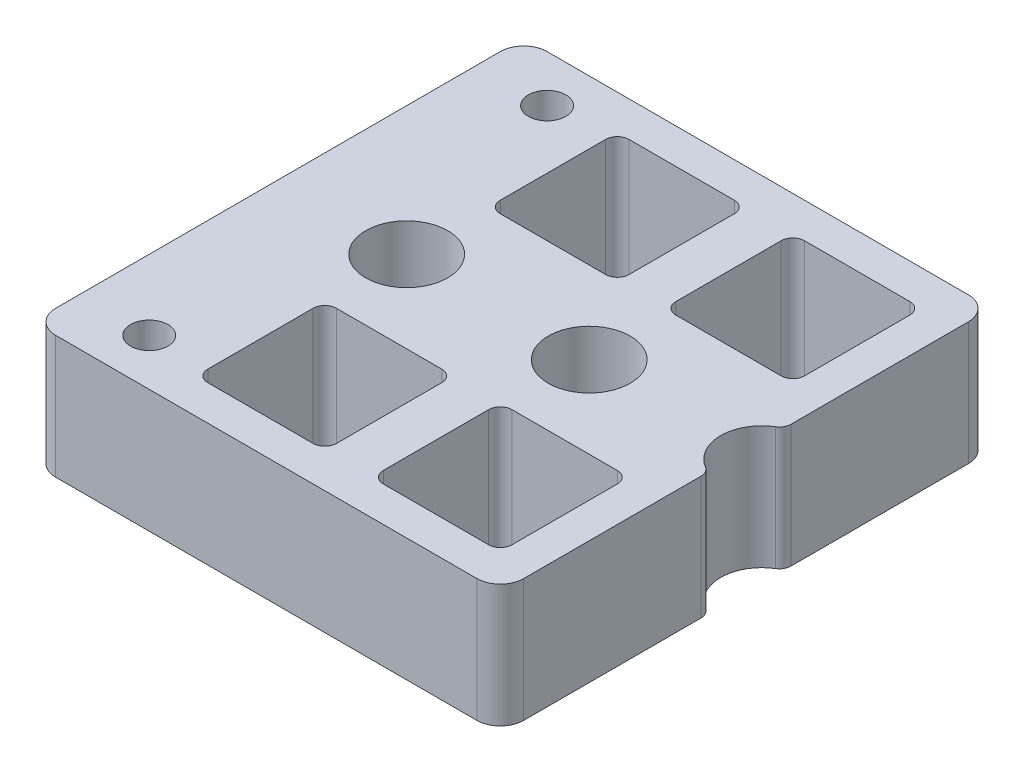
SolidWorks part; units mm, degrees
material "ABS"
ref_plane "前视基准面" through (0, 0, 0) normal (0, 0, 1) x (1, 0, 0)
ref_plane "上视基准面" through (0, 0, 0) normal (0, 1, 0) x (1, 0, 0)
ref_plane "右视基准面" through (0, 0, 0) normal (1, 0, 0) x (0, 0, -1)
other "Configuration Table"
sketch "草图1" plane through (0, 0, 0) normal (0, 1, 0) x (1, 0, 0)
  line L0 (-15, 19.7671) -> (-15, -49.3288) construction
  line L1 (-40, 45) -> (-25, 45)
  line L2 (-40, 45) -> (-40, -45) construction
  line L3 (-40, -45) -> (-25, -45)
  line L4 (-25, 45) -> (-25, -45)
  line L5 (-115, 21) -> (-41, 21) construction
  line L6 (-115, 21) -> (-115, -21)
  line L7 (-115, -21) -> (-41, -21) construction
  line L8 (-41, 21) -> (-41, -21) construction
  line L9 (0, 0) -> (-115, 0) construction
  line L10 (-115, 21) -> (-40, 45)
  line L11 (-115, -21) -> (-40, -45)
  line L12 (-98.5945, 21) -> (-40, 39.7502)
  line L13 (-40, 39.7502) -> (-40, 21)
  line L14 (-40, 21) -> (-98.5945, 21)
  line L15 (-40, -21) -> (-98.5945, -21)
  line L16 (-98.5945, -21) -> (-40, -39.7502)
  line L17 (-40, -39.7502) -> (-40, -21)
  line L18 (-32.5, 45) -> (-32.5, -45) construction
  line L19 (-79, 21) -> (-79, -21) construction
  line L20 (-45, 21) -> (-45, -21)
  line L21 (-115, -21) -> (-98.5945, -21)
  line L22 (-115, 21) -> (-98.5945, 21)
  line L23 (-85, 21) -> (-85, -21)
  circle A0 centre (-32.5, 0) radius 1.6
  circle A1 centre (-32.5, -30) radius 1.6
  circle A2 centre (-32.5, 30) radius 1.6
  circle A3 centre (-79, 17) radius 1.6
  circle A4 centre (-79, -17) radius 1.6
  circle A5 centre (-94, 0) radius 1.6
  circle A6 centre (-69, 0) radius 1.6
  dimension "D9" = 3.2
  dimension "D10" = 3.2
  dimension "D11" = 3.2
  dimension "D14" = 3.2
  dimension "D15" = 3.2
  dimension "D19" = 3.2
  dimension "D20" = 3.2
  dimension "D1" = 26
  dimension "D2" = 74
  dimension "D3" = 15
  dimension "D4" = 25
  dimension "D5" = 15
  dimension "D6" = 42
  dimension "D7" = 90
  dimension "D8" = 5
  dimension "D12" = 15
  dimension "D13" = 15
  dimension "D16" = 17
  dimension "D17" = 17
  dimension "D18" = 38
  dimension "D21" = 25
  dimension "D22" = 28
  dimension "D23" = 70
  dimension "D24" = 6
extrude "凸台-拉伸1" add sketch "草图1" along normal blind 10.5 contours L14 L23 L15 L20 A6 A4 A3
fillet "圆角1" radius 2 4 edges at (-45, 5.25, -21) (-45, 5.25, 21) (-85, 5.25, 21) (-85, 5.25, -21)
sketch "草图2" plane through (0, 10.5, 0) normal (0, 1, 0) x (1, 0, 0)
  line L0 (-85, 0) -> (-45, 0) construction
  line L1 (-85, 19) -> (-85, -19) construction
  line L2 (-45, 19) -> (-45, -19) construction
  circle A0 centre (-74, 0) radius 1.6
  circle A1 centre (-44, 0) radius 1.6
  circle A2 centre (-58.4, 0) radius 1.6
  dimension "D1" = 3.2
  dimension "D2" = 3.2
  dimension "D4" = 30
  dimension "D5" = 3.2
  dimension "D6" = 15.6
  dimension "D3" = 11
extrude "切除-拉伸1" cut sketch "草图2" against normal through all
sketch "草图3" plane through (0, 10.5, 0) normal (0, 1, 0) x (1, 0, 0)
  circle A0 centre (-69, 0) radius 1.6 construction
  circle A1 centre (-69, 0) radius 1.6
extrude "凸台-拉伸2" add sketch "草图3" against normal up to surface (10.5 mm away) up to face at (-74, 0, 1.6)
sketch "草图4" plane through (0, 10.5, 0) normal (0, 1, 0) x (1, 0, 0)
  circle A0 centre (-74, 0) radius 3.5
  circle A1 centre (-58.4, 0) radius 3.5
  circle A2 centre (-43.6631, 0) radius 3.5
  dimension "D1" = 7
  dimension "D2" = 7
  dimension "D3" = 7
extrude "切除-拉伸2" cut sketch "草图4" against normal blind 5
sketch "草图5" plane through (0, 5.5, 0) normal (0, 1, 0) x (1, 0, 0)
  line L0 (-45, 3.2346) -> (-45, -3.2346)
  arc A0 (-45, 3.2346) -> (-45, -3.2346) centre (-43.6631, 0) ccw construction
  arc A1 (-45, 3.2346) -> (-45, -3.2346) centre (-43.6631, 0) ccw
extrude "切除-拉伸3" cut sketch "草图5" against normal through all
sketch "草图6" plane through (0, 10.5, 0) normal (0, 1, 0) x (1, 0, 0)
  line L0 (-47, 21) -> (-83, 21) construction
  line L1 (-74, 7) -> (-48, 7)
  line L2 (-74, 7) -> (-74, 18)
  line L3 (-74, 18) -> (-48, 18)
  line L4 (-48, 7) -> (-48, 18)
  line L5 (-74, 7) -> (-48, 18) construction
  line L6 (-74, 18) -> (-48, 7) construction
  line L7 (-45, 19) -> (-45, 3.2346) construction
  line L8 (-85, 19) -> (-85, -19) construction
  line L9 (-85, 0) -> (-47.1631, 0) construction
  line L10 (-61, 18) -> (-61, 7) construction
  line L11 (-63, 18) -> (-63, 7)
  line L12 (-59, 18) -> (-59, 7)
  line L13 (-61, -18) -> (-61, -7) construction
  line L14 (-74, -18) -> (-48, -7) construction
  line L15 (-74, -7) -> (-48, -18) construction
  line L16 (-59, -18) -> (-59, -7)
  line L17 (-63, -18) -> (-63, -7)
  line L18 (-48, -7) -> (-48, -18)
  line L19 (-74, -18) -> (-48, -18)
  line L20 (-74, -7) -> (-74, -18)
  line L21 (-74, -7) -> (-48, -7)
  arc A0 (-45, 3.2346) -> (-45, -3.2346) centre (-43.6631, 0) ccw construction
  point P0 (-61, 12.5)
  point P32 (-61, -12.5)
  dimension "D1" = 3
  dimension "D2" = 3
  dimension "D3" = 11
  dimension "D4" = 11
  dimension "D5" = 2
  dimension "D6" = 2
extrude "切除-拉伸4" cut sketch "草图6" against normal through all contours L11 L3 L2 L1 | L3 L12 L1 L4 | L21 L20 L19 L17 | L21 L16 L19 L18
fillet "圆角2" radius 1 18 edges at (-45, 5.25, -3.2346) (-45, 5.25, 3.2346) (-48, 5.25, -18) (-48, 5.25, -7) (-59, 5.25, -7) (-59, 5.25, -18) (-48, 5.25, 7) (-48, 5.25, 18) (-59, 5.25, 18) (-59, 5.25, 7) (-63, 5.25, -7) (-63, 5.25, -18) (-63, 5.25, 7) (-63, 5.25, 18) (-74, 5.25, 18) (-74, 5.25, 7) (-74, 5.25, -7) (-74, 5.25, -18)
